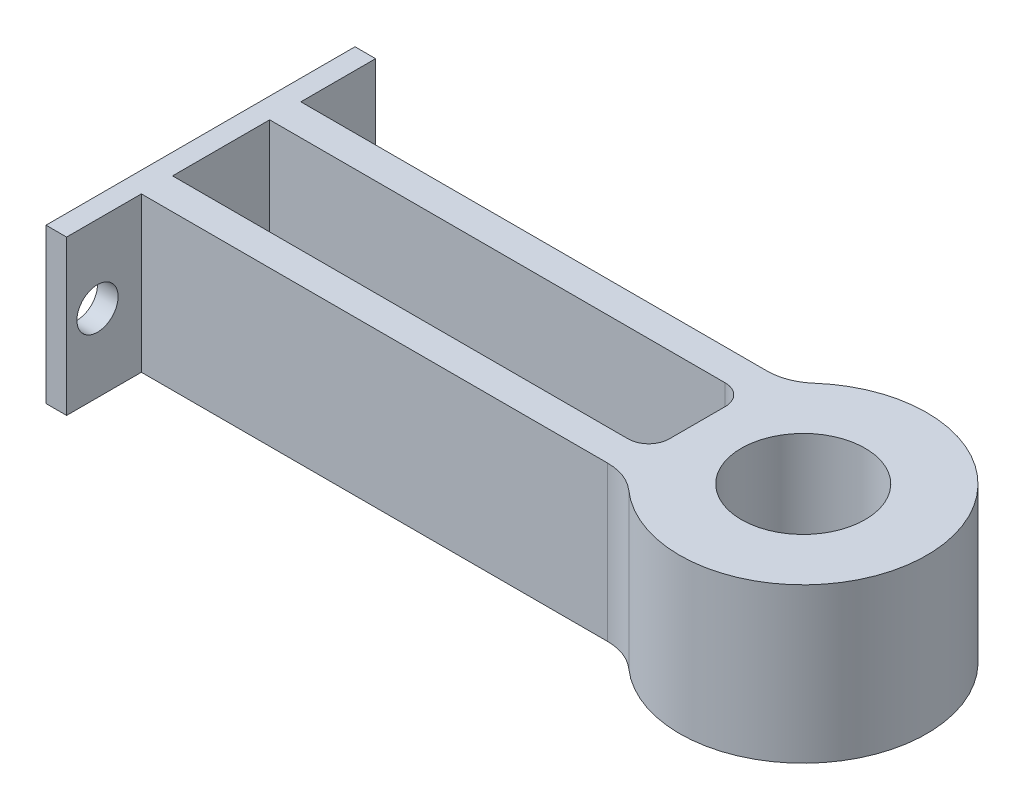
SolidWorks part; units mm, degrees
ref_plane "Front Plane" through (0, 0, 0) normal (0, 0, 1) x (1, 0, 0)
ref_plane "Top Plane" through (0, 0, 0) normal (0, 1, 0) x (1, 0, 0)
ref_plane "Right Plane" through (0, 0, 0) normal (1, 0, 0) x (0, 0, -1)
sketch "草图1" plane through (0, 0, 0) normal (0, 1, 0) x (1, 0, 0)
  line L0 (-10.2881, -6.177) -> (-10.2881, 6.177)
  arc A1 (-10.2881, -6.177) -> (-10.2881, 6.177) centre (0, 0) ccw
extrude "凸台-拉伸1" add sketch "草图1" along normal blind 15 contours A1 L0
sketch "草图2" plane through (0, 15, 0) normal (0, 1, 0) x (1, 0, 0)
  circle A0 centre (0, 0) radius 6.01
sketch "草图4" plane through (-10.2881, 0, 0) normal (-1, 0, 0) x (0, 0, 1)
  line L0 (0, 0) -> (0, 15)
  line L1 (6.177, 0) -> (-6.177, 0) construction
  line L2 (6.177, 15) -> (-6.177, 15) construction
  line L3 (-7.7395, 0) -> (-7.7395, 15)
  line L4 (-7.7395, 0) -> (7.7395, 0)
  line L5 (0, 0) -> (0, 15)
  line L6 (-7.7395, 15) -> (7.7395, 15)
  line L7 (7.7395, 0) -> (7.7395, 15)
  line M6 (-6.177, 0) -> (6.177, 0)
  line M7 (6.177, 0) -> (6.177, 15)
  line M8 (6.177, 15) -> (-6.177, 15)
  line M9 (-6.177, 15) -> (-6.177, 0)
extrude "凸台-拉伸3" add sketch "草图4" against normal blind 5 contours L4 L7 L6 M7 | L6 L3 L4 M9 | L0 M6 M8 M9 | L0 M6 M7 M8
extrude "切除-拉伸2" cut sketch "草图2" against normal blind 200 contours A0
sketch "草图7" plane through (-10.2881, 0, 0) normal (-1, 0, 0) x (0, 0, 1)
  line L0 (0, 0) -> (0, 15)
  line L1 (7.7395, 0) -> (-7.7395, 0) construction
  line L2 (7.7395, 15) -> (-7.7395, 15) construction
  line L3 (-7.7395, 15) -> (-4.7136, 15)
  line L4 (7.7395, 0) -> (4.7136, 0)
  line L5 (7.7395, 0) -> (7.7395, 15)
  line L6 (7.7395, 15) -> (4.7136, 15)
  line L7 (4.7136, 0) -> (4.7136, 15)
  line L8 (-7.7395, 0) -> (-7.7395, 15)
  line L9 (-7.7395, 0) -> (-4.7136, 0)
  line L10 (-4.7136, 0) -> (-4.7136, 15)
  line M6 (-7.7395, 0) -> (7.7395, 0)
  line M7 (7.7395, 0) -> (7.7395, 15)
  line M8 (7.7395, 15) -> (-7.7395, 15)
  line M9 (-7.7395, 15) -> (-7.7395, 0)
extrude "凸台-拉伸4" add sketch "草图7" along normal blind 46.224 contours L7 M6 M7 M8 | L10 M6 M8 M9
fillet "圆角1" radius 2 2 edges at (-10.2881, 7.5, -4.7136) (-10.2881, 7.5, 4.7136)
fillet "圆角2" radius 5 2 edges at (-9.1706, 7.5, -7.7395) (-9.1706, 7.5, 7.7395)
sketch "草图8" plane through (-56.5121, 0, 0) normal (-1, 0, 0) x (0, 0, 1)
  line L2 (15, 0) -> (15, 15)
  line L5 (-15, 15) -> (15, 15)
  line L6 (-15, 0) -> (-15, 15)
  line L7 (15, 0) -> (-15, 0)
  circle A3 centre (-12, 7.5) radius 2
  circle A4 centre (12, 7.5) radius 2
  line M5 (4.7136, 15) -> (4.7136, 0)
  line M6 (4.7136, 0) -> (7.7395, 0)
  line M7 (7.7395, 0) -> (7.7395, 15)
  line M8 (7.7395, 15) -> (4.7136, 15)
extrude "凸台-拉伸5" add sketch "草图8" along normal blind 2 contours L7 L2 L5 A4 M7 | L7 L5 L6 A3 M5 | M8 M5 M6 M7
